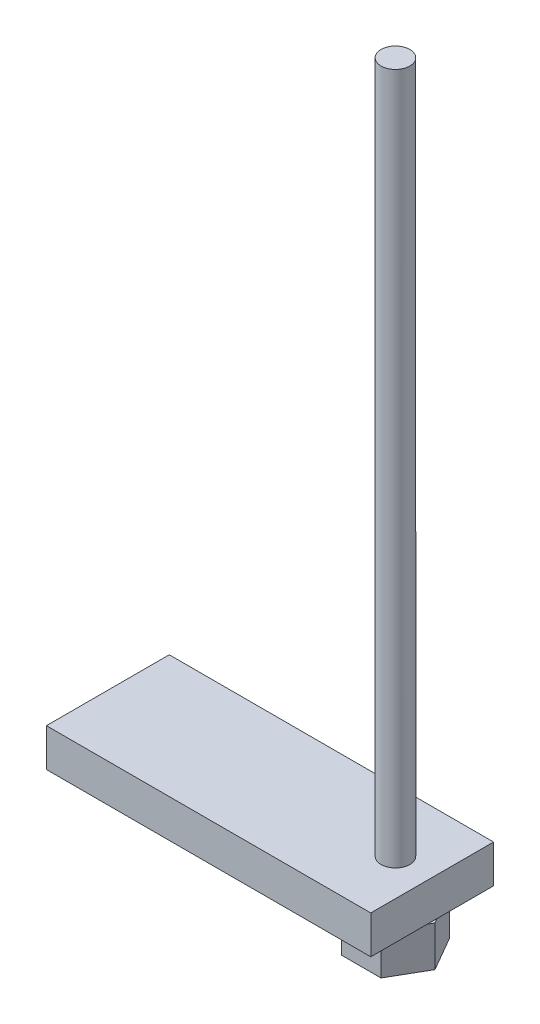
SolidWorks part; units mm, degrees
ref_plane "Front Plane" through (0, 0, 0) normal (0, 0, 1) x (1, 0, 0)
ref_plane "Top Plane" through (0, 0, 0) normal (0, 1, 0) x (1, 0, 0)
ref_plane "Right Plane" through (0, 0, 0) normal (1, 0, 0) x (0, 0, -1)
sketch "Sketch1" plane through (0, 0, 0) normal (0, 1, 0) x (1, 0, 0)
  line L1 (-33.8745, -12.828) -> (33.8745, -12.828)
  line L2 (-33.8745, -12.828) -> (-33.8745, 12.828)
  line L3 (-33.8745, 12.828) -> (33.8745, 12.828)
  line L4 (33.8745, -12.828) -> (33.8745, 12.828)
  line L5 (-33.8745, -12.828) -> (33.8745, 12.828) construction
  line L6 (-33.8745, 12.828) -> (33.8745, -12.828) construction
  point P0 (0, 0)
  dimension "D1" = 67.749
  dimension "D2" = 25.656
extrude "Boss-Extrude1" add sketch "Sketch1" along normal blind 7.9375
sketch "Sketch2" plane through (0, 7.9375, 0) normal (0, 1, 0) x (1, 0, 0)
  line L0 (0, 0) -> (33.8745, 0) construction
  line L1 (33.8745, -12.828) -> (33.8745, 12.828) construction
  circle A0 centre (26.2085, 0) radius 3
  dimension "D1" = 6
  dimension "D2" = 7.666
extrude "Boss-Extrude2" add sketch "Sketch2" along normal blind 144.4625
sketch "Sketch3" plane through (0, 0, 0) normal (0, -1, 0) x (1, 0, 0)
  line L1 (22.0835, -7.1447) -> (30.3335, -7.1447)
  line L2 (30.3335, -7.1447) -> (34.4585, 0)
  line L3 (34.4585, 0) -> (30.3335, 7.1447)
  line L4 (30.3335, 7.1447) -> (22.0835, 7.1447)
  line L5 (22.0835, 7.1447) -> (17.9585, 0)
  line L6 (17.9585, 0) -> (22.0835, -7.1447)
  circle A0 centre (26.2085, 0) radius 7.1447 construction
  circle A1 centre (26.2085, 0) radius 3
  circle A2 centre (26.2085, 0) radius 3 construction
  point P0 (26.9839, 3.9817)
  point P2 (29.3609, -0.0143)
  dimension "D2" = 16.5
  dimension "D1" = 0
extrude "Boss-Extrude4" add sketch "Sketch3" along normal blind 8.448
